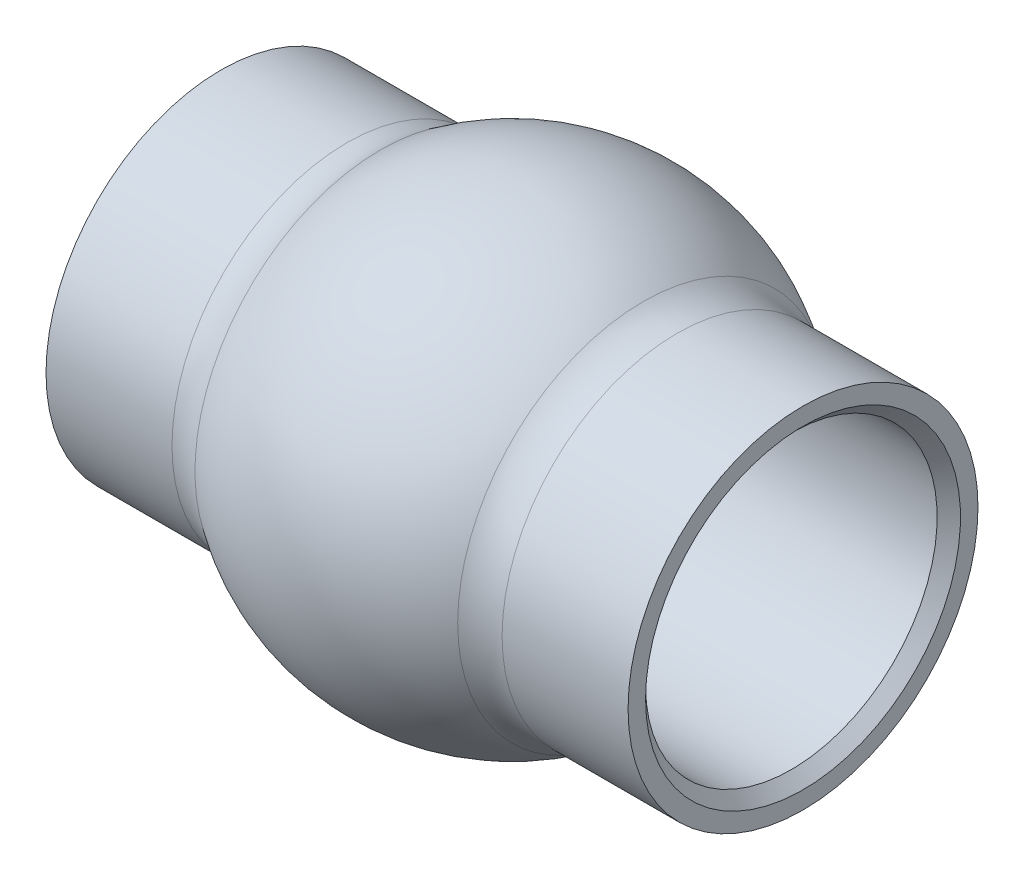
SolidWorks part; units mm, degrees
material "AISI 316 Annealed Stainless Steel Bar (SS)"
ref_plane "Front Plane" through (0, 0, 0) normal (0, 0, 1) x (1, 0, 0)
ref_plane "Top Plane" through (0, 0, 0) normal (0, 1, 0) x (1, 0, 0)
ref_plane "Right Plane" through (0, 0, 0) normal (1, 0, 0) x (0, 0, -1)
sketch "Sketch1" plane through (0, 0, 0) normal (0, 0, 1) x (1, 0, 0)
  line L0 (-29.7402, 0) -> (-4.5895, 0) construction
  line L1 (-12.6746, 6.35) -> (12.6746, 6.35)
  line L2 (12.6746, 6.35) -> (12.6746, 7.62)
  line L3 (12.6746, 7.62) -> (6.3296, 7.62)
  line L4 (-12.6746, 7.62) -> (-12.6746, 6.35)
  line L5 (-6.3296, 7.62) -> (-12.6746, 7.62)
  arc A0 (6.3296, 7.62) -> (-6.3296, 7.62) centre (0, 0) ccw
  dimension "D1" = 12.7
  dimension "D3" = 25.3492
  dimension "D4" = 19.812
  dimension "D2" = 15.24
revolve "Revolve1" add sketch "Sketch1" angle 360 about L0
fillet "Fillet1" radius 2.54 2 edges at (-6.3296, 0, 7.62) (6.3296, 0, 7.62)
chamfer "Chamfer1" distance 0.508 angle 45 2 edges at (-12.6746, 0, 6.35) (12.6746, 0, 6.35)
